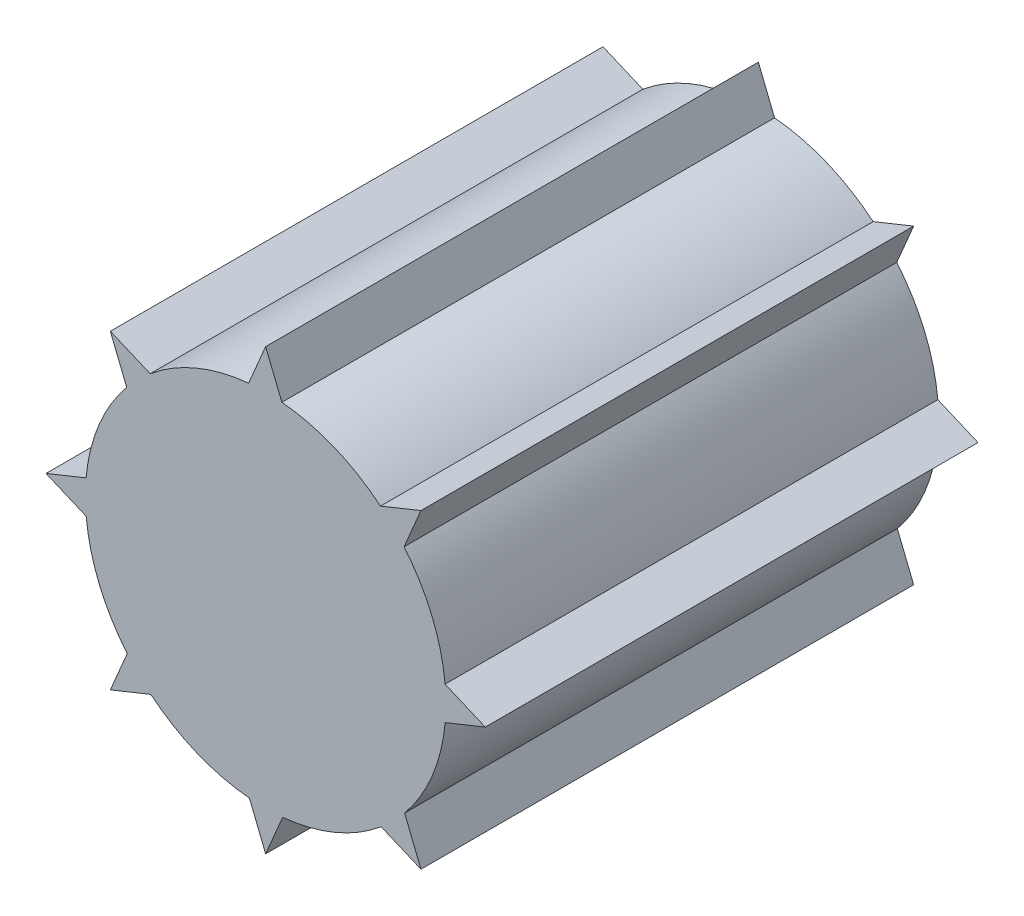
SolidWorks part; units mm, degrees
ref_plane "Alzado" through (0, 0, 0) normal (0, 0, 1) x (1, 0, 0)
ref_plane "Planta" through (0, 0, 0) normal (0, 1, 0) x (1, 0, 0)
ref_plane "Vista lateral" through (0, 0, 0) normal (1, 0, 0) x (0, 0, -1)
sketch "Croquis1" plane through (0, 0, 0) normal (0, 0, 1) x (1, 0, 0)
  line L0 (-2.9404, 30.9582) -> (0, 37.8917)
  line L1 (0, 37.8917) -> (2.7987, 30.9713)
  line L2 (26.7935, 26.7935) -> (23.879, 19.9211)
  line L3 (19.8116, 23.9699) -> (26.7935, 26.7935)
  line L4 (37.8917, 0) -> (30.9713, -2.7987)
  line L5 (30.9582, 2.9404) -> (37.8917, 0)
  line L6 (26.7935, -26.7935) -> (19.9211, -23.879)
  line L7 (23.9699, -19.8116) -> (26.7935, -26.7935)
  line L8 (0, -37.8917) -> (-2.7987, -30.9713)
  line L9 (2.9404, -30.9582) -> (0, -37.8917)
  line L10 (-26.7935, -26.7935) -> (-23.879, -19.9211)
  line L11 (-19.8116, -23.9699) -> (-26.7935, -26.7935)
  line L12 (-37.8917, 0) -> (-30.9713, 2.7987)
  line L13 (-30.9582, -2.9404) -> (-37.8917, 0)
  line L14 (-26.7935, 26.7935) -> (-19.9211, 23.879)
  line L15 (-23.9699, 19.8116) -> (-26.7935, 26.7935)
  arc A0 (-2.9404, 30.9582) -> (-19.9211, 23.879) centre (0, 0) ccw
  arc A1 (-23.9699, 19.8116) -> (-30.9713, 2.7987) centre (0, 0) ccw
  arc A2 (-30.9582, -2.9404) -> (-23.879, -19.9211) centre (0, 0) ccw
  arc A3 (-19.8116, -23.9699) -> (-2.7987, -30.9713) centre (0, 0) ccw
  arc A4 (2.9404, -30.9582) -> (19.9211, -23.879) centre (0, 0) ccw
  arc A5 (23.9699, -19.8116) -> (30.9713, -2.7987) centre (0, 0) ccw
  arc A6 (30.9582, 2.9404) -> (23.879, 19.9211) centre (0, 0) ccw
  arc A7 (19.8116, 23.9699) -> (2.7987, 30.9713) centre (0, 0) ccw
  point P29 (0, 0)
  dimension "D1" = 8
extrude "Saliente-Extruir1" add sketch "Croquis1" along normal blind 85
